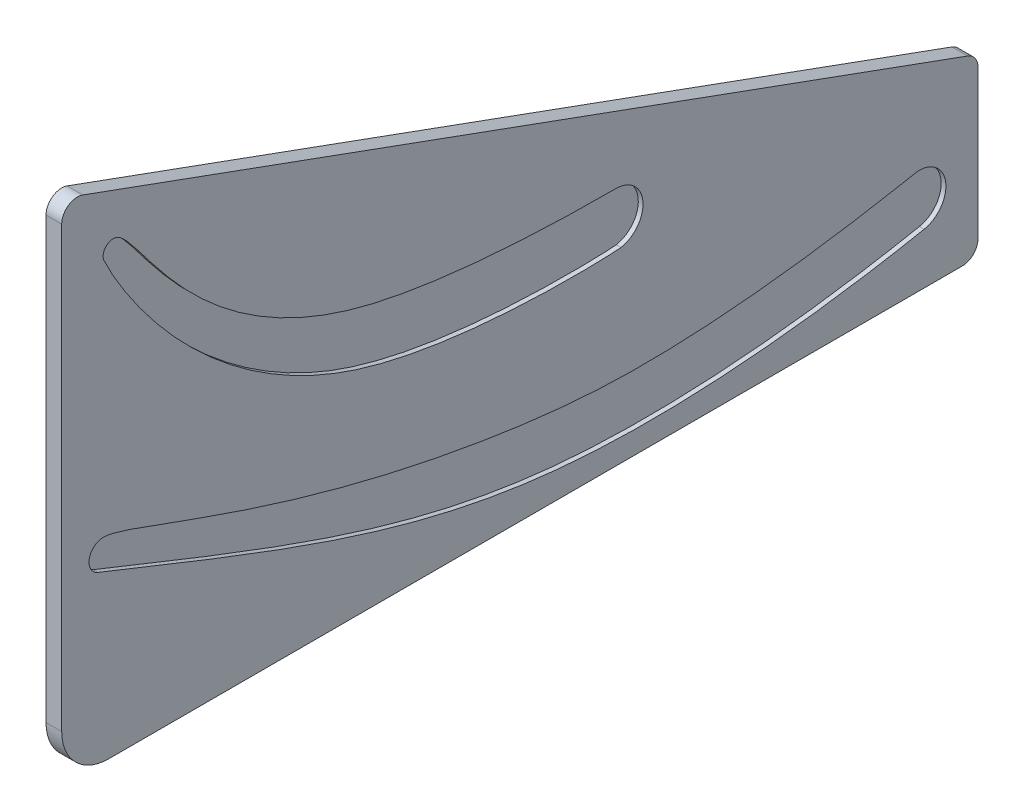
SolidWorks part; units mm, degrees
ref_plane "Front Plane" through (0, 0, 0) normal (0, 0, 1) x (1, 0, 0)
ref_plane "Top Plane" through (0, 0, 0) normal (0, 1, 0) x (1, 0, 0)
ref_plane "Right Plane" through (0, 0, 0) normal (1, 0, 0) x (0, 0, -1)
sketch "Sketch1" plane through (0, 0, 0) normal (1, 0, 0) x (0, 0, -1)
  line L0 (0, -14.2815) -> (0, -294.2815)
  line L1 (0, 29.2892) -> (0, -29.2892) construction
  line L2 (30, -324.2815) -> (573.8156, -324.2815)
  line L3 (583.8156, -314.2815) -> (583.8156, -219.4936)
  line L4 (577.2358, -210.0966) -> (13.4202, -4.8846)
  arc A0 (30, -324.2815) -> (0, -294.2815) centre (30, -294.2815) cw
  arc A1 (573.8156, -324.2815) -> (583.8156, -314.2815) centre (573.8156, -314.2815) ccw
  arc A2 (583.8156, -219.4936) -> (577.2358, -210.0966) centre (573.8156, -219.4936) ccw
  arc A3 (13.4202, -4.8846) -> (0, -14.2815) centre (10, -14.2815) ccw
  point P9 (0, -324.2815)
  point P16 (0, 0)
  dimension "D2" = 30
  dimension "D3" = 10
  dimension "D1" = 70
  dimension "D4" = 280
  dimension "D5" = 600
extrude "Boss-Extrude1" add sketch "Sketch1" along normal blind 10
sketch "Sketch2" plane through (10, 0, 0) normal (1, 0, 0) x (0, 0, -1)
  arc A0 (23.1622, -218.0173) -> (26.7381, -200.3183) centre (26.5742, -209.4959) cw
  arc A1 (549.474, -291.831) -> (546.1549, -257.731) centre (546.1581, -274.9423) ccw
  arc A2 (26.9502, -47.7372) -> (35.1249, -39.1544) centre (32.8168, -45.1404) cw
  arc A3 (356.3201, -205.3163) -> (353.1695, -171.1817) centre (353.1695, -188.3944) ccw
  spline S0 degree 3 poles (23.1622, -218.0173) (143.0808, -266.0342) (284.6699, -324.5722) (474.7501, -306.5023) (549.474, -291.831) knots 0 0 0 0 0.576112 1 1 1 1
  spline S1 degree 3 poles (26.7381, -200.3183) (45.9144, -200.6608) (151.3211, -255.5104) (414.8803, -286.3851) (542.4311, -257.7317) (546.1549, -257.731) knots 0 0 0 0 0.560935 0.660935 1 1 1 1
  spline S2 degree 3 poles (26.9502, -47.7372) (35.3127, -66.6296) (121.3965, -217.9891) (352.8389, -205.9644) (356.3201, -205.3163) knots 0 0 0 0 0.590315 1 1 1 1
  spline S3 degree 3 poles (35.1249, -39.1544) (50.603, -45.1224) (99.0425, -170.6619) (331.224, -171.1817) (353.1695, -171.1817) knots 0 0 0 0 0.639196 1 1 1 1
sketch "Sketch3" plane through (0, 0, 0) normal (-1, 0, 0) x (0, 0, 1)
  arc A2 (-23.1622, -218.0173) -> (-26.7381, -200.3183) centre (-26.5742, -209.4959) ccw
  arc A3 (-546.1549, -257.731) -> (-549.474, -291.831) centre (-546.1581, -274.9423) ccw
  arc A4 (-23.1622, -218.0173) -> (-26.7381, -200.3183) centre (-26.5742, -209.4959) ccw
  arc A5 (-546.1549, -257.731) -> (-549.474, -291.831) centre (-546.1581, -274.9423) ccw
  arc A6 (-26.9502, -47.7372) -> (-35.1249, -39.1544) centre (-32.8168, -45.1404) ccw
  arc A7 (-353.1695, -171.1817) -> (-356.3201, -205.3163) centre (-353.1695, -188.3944) ccw
  arc A8 (-26.9502, -47.7372) -> (-35.1249, -39.1544) centre (-32.8168, -45.1404) ccw
  arc A9 (-353.1695, -171.1817) -> (-356.3201, -205.3163) centre (-353.1695, -188.3944) ccw
  spline S2 degree 3 poles (-1816.3187, -2605.5409) (75.9737, 231.5319) (247.8188, -208.7531) (-624.0722, -310.8909) (-1042.2542, -16.1976) (2292.0508, -1228.213) knots -1.514422 -1.514422 -1.514422 -1.514422 0.560935 0.660935 1.793718 1.793718 1.793718 1.793718 only from (-26.7381, -200.3183) to (-546.1549, -257.731)
  spline S3 degree 3 poles (2381.1668, -869.8797) (-1836.6269, 336.9299) (-160.0228, -831.4717) (182.4388, 107.8527) (2926.7447, 268.4202) knots -2.671816 -2.671816 -2.671816 -2.671816 0.423888 2.573484 2.573484 2.573484 2.573484 only from (-549.474, -291.831) to (-23.1622, -218.0173)
  spline S4 degree 3 poles (-26.7381, -200.3183) (-45.9144, -200.6608) (-151.3211, -255.5104) (-414.8803, -286.3851) (-542.4311, -257.7317) (-546.1549, -257.731) knots 0 0 0 0 0.560935 0.660935 1 1 1 1
  spline S5 degree 3 poles (-549.474, -291.831) (-474.7501, -306.5023) (-284.6699, -324.5722) (-143.0808, -266.0342) (-23.1622, -218.0173) knots 0 0 0 0 0.423888 1 1 1 1
  spline S6 degree 3 poles (620.0267, -2965.5435) (-330.0266, 628.3163) (484.1929, -482.6485) (-970.471, -49.8454) (2628.5866, -498.6084) knots -1.524676 -1.524676 -1.524676 -1.524676 0.639196 1.989327 1.989327 1.989327 1.989327 only from (-35.1249, -39.1544) to (-353.1695, -171.1817)
  spline S7 degree 3 poles (2605.5885, -677.7833) (-930.4728, -32.6201) (328.2216, -605.2679) (-87.5838, 704.2328) (-600.8148, -2989.1172) knots -0.959059 -0.959059 -0.959059 -0.959059 0.409685 2.43502 2.43502 2.43502 2.43502 only from (-356.3201, -205.3163) to (-26.9502, -47.7372)
  spline S8 degree 3 poles (-35.1249, -39.1544) (-50.603, -45.1224) (-99.0425, -170.6619) (-331.224, -171.1817) (-353.1695, -171.1817) knots 0 0 0 0 0.639196 1 1 1 1
  spline S9 degree 3 poles (-356.3201, -205.3163) (-352.8389, -205.9644) (-121.3965, -217.9891) (-35.3127, -66.6296) (-26.9502, -47.7372) knots 0 0 0 0 0.409685 1 1 1 1
  dimension "D1" = 0
  dimension "D2" = 0
extrude "Cut-Extrude2" cut sketch "Sketch2" against normal blind 3
sketch "Sketch4" plane through (0, 0, 0) normal (-1, 0, 0) x (0, 0, 1)
  line L0 (-561.5873, -305.6301) -> (-27.292, -305.6301) construction
  line L1 (-561.5873, -296.6301) -> (-27.292, -296.6301)
  line L2 (-561.5873, -314.6301) -> (-27.292, -314.6301)
  arc A0 (-561.5873, -296.6301) -> (-561.5873, -314.6301) centre (-561.5873, -305.6301) ccw
  arc A1 (-27.292, -314.6301) -> (-27.292, -296.6301) centre (-27.292, -305.6301) ccw
  point P2 (-294.4396, -305.6301)
  point P7 (-35.8907, -310.5184)
  point P8 (0, 0)
  point P9 (0, 0)
  point P10 (-30.5241, -306.7075)
  point P11 (-35.3723, -307.7848)
  point P12 (-27.292, -305.6301)
  dimension "D1" = 18
extrude "Cut-Extrude3" cut sketch "Sketch4" against normal blind 3
